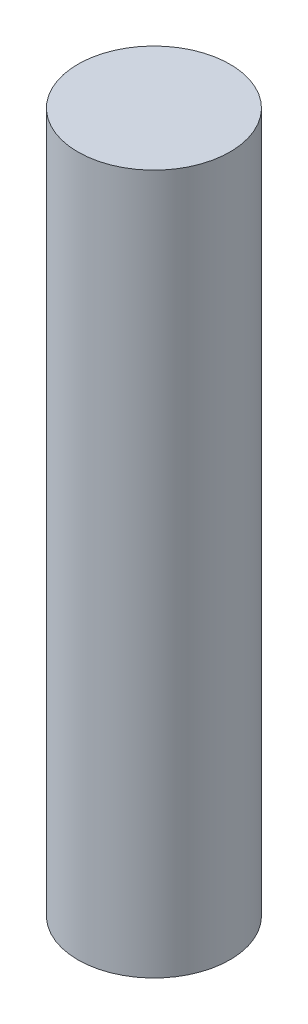
SolidWorks part; units mm, degrees
ref_plane "前视基准面" through (0, 0, 0) normal (0, 0, 1) x (1, 0, 0)
ref_plane "上视基准面" through (0, 0, 0) normal (0, 1, 0) x (1, 0, 0)
ref_plane "右视基准面" through (0, 0, 0) normal (1, 0, 0) x (0, 0, -1)
sketch "草图1" plane through (0, 0, 0) normal (0, 1, 0) x (1, 0, 0)
  circle A0 centre (0, 0) radius 5
  dimension "D1" = 10
extrude "凸台-拉伸3" add sketch "草图1" along normal blind 46
